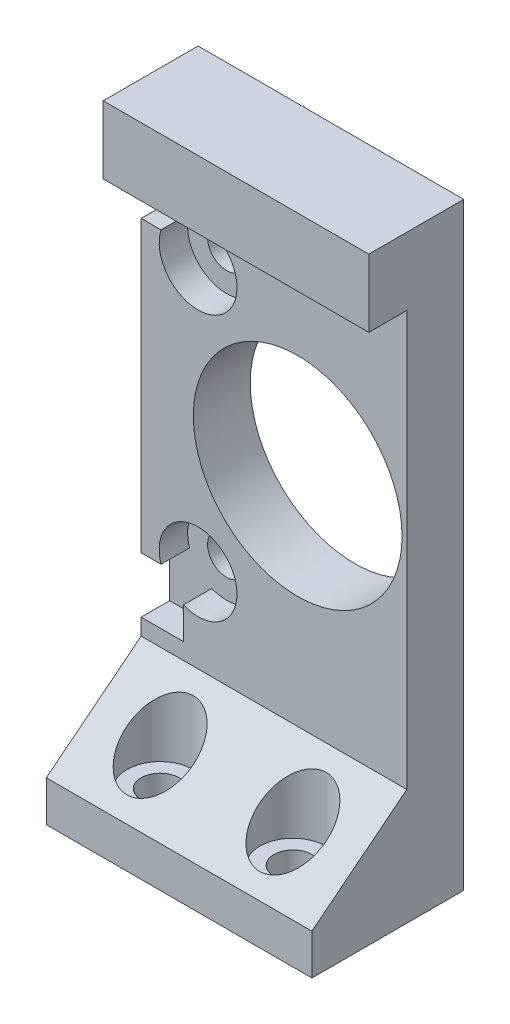
SolidWorks part; units mm, degrees
material "ABS"
ref_plane "Front Plane" through (0, 0, 0) normal (0, 0, 1) x (1, 0, 0)
ref_plane "Top Plane" through (0, 0, 0) normal (0, 1, 0) x (1, 0, 0)
ref_plane "Right Plane" through (0, 0, 0) normal (1, 0, 0) x (0, 0, -1)
sketch "Sketch1" plane through (0, 0, 0) normal (0, 0, 1) x (1, 0, 0)
  line L1 (-76.1871, 64.9281) -> (16.8129, 64.9281)
  line L2 (-76.1871, 64.9281) -> (-76.1871, -35.0719)
  line L3 (-76.1871, -35.0719) -> (16.8129, -35.0719)
  line L4 (16.8129, 64.9281) -> (16.8129, -35.0719)
  dimension "D1" = 93
  dimension "D2" = 100
extrude "Boss-Extrude2" add sketch "Sketch1" along normal blind 10 contours L1 L4 L3 L2
sketch "Sketch3" plane through (0, 0, 0) normal (0, 0, -1) x (-1, 0, 0)
  line L0 (76.1871, -35.0719) -> (-16.8129, -35.0719) construction
  line L1 (-16.8129, 64.9281) -> (-6.8129, 64.9281)
  line L2 (-16.8129, 64.9281) -> (-16.8129, -35.0719)
  line L3 (-16.8129, -35.0719) -> (-6.8129, -35.0719)
  line L4 (-6.8129, 64.9281) -> (-6.8129, -35.0719)
  line L5 (-16.8129, 64.9281) -> (-16.8129, -35.0719) construction
  dimension "D1" = 0
  dimension "D2" = 0
  dimension "D3" = 10
  dimension "D4" = 100
sketch "Sketch4" plane through (16.8129, 0, 0) normal (1, 0, 0) x (0, 0, -1)
  line L0 (-10, 64.9281) -> (-10, -35.0719) construction
  line L1 (-10, -5.0719) -> (0.01, -5.0719)
  line L2 (-10, -5.0719) -> (-10, -20.0719)
  line L3 (-10, -20.0719) -> (0.01, -20.0719)
  line L4 (0.01, -5.0719) -> (0.01, -20.0719)
  line L6 (-10, -35.0719) -> (0, -35.0719) construction
  dimension "D1" = 15
  dimension "D2" = 15
extrude "Boss-Extrude4" add sketch "Sketch4" along normal blind 24
sketch "Sketch5" plane through (0, -5.0719, 0) normal (0, 1, 0) x (1, 0, 0)
  line L0 (40.8129, -10) -> (16.8129, -10) construction
  line L2 (16.8129, 0) -> (16.8129, -10) construction
  circle A0 centre (26.8129, -5) radius 2
  dimension "D2" = 4
  dimension "D3" = 10
  dimension "D1" = 5
extrude "Cut-Extrude1" cut sketch "Sketch5" against normal blind 50
sketch "Sketch6" plane through (0, 0, 10) normal (0, 0, -1) x (-1, 0, 0)
  line L2 (76.1871, -35.0719) -> (-16.8129, -35.0719) construction
  line L3 (-16.8129, 64.9281) -> (-16.8129, -35.0719) construction
  circle A0 centre (-1.8129, -24.5719) radius 7.5
  dimension "D1" = 15
  dimension "D2" = 10.5
  dimension "D3" = 15
sketch "Sketch7" plane through (0, 0, 0) normal (0, 0, -1) x (-1, 0, 0)
  circle A0 centre (24.1871, 36.9281) radius 11
  circle A1 centre (24.1871, 36.9281) radius 9.3 construction
  dimension "D1" = 22
extrude "Cut-Extrude3" cut sketch "Sketch7" against normal blind 50
sketch "Sketch14" plane through (0, 0, 10) normal (0, 0, 1) x (1, 0, 0)
  line L0 (16.8129, 64.9281) -> (16.8129, -5.0719) construction
  line L1 (-44.6871, 15.7891) -> (16.8129, 15.7891)
  line L2 (-44.6871, 15.7891) -> (-44.6871, 57.7891)
  line L3 (-44.6871, 57.7891) -> (16.8129, 57.7891)
  line L4 (16.8129, 15.7891) -> (16.8129, 57.7891)
  dimension "D1" = 42
  dimension "D3" = 61.5
extrude "Cut-Extrude8" cut sketch "Sketch14" against normal blind 4
sketch "Sketch15" plane through (0, 0, 0) normal (0, 0, -1) x (-1, 0, 0)
  circle A0 centre (24.1871, 36.9281) radius 10
  circle A1 centre (24.1871, 36.9281) radius 11 construction
  dimension "D1" = 20
  dimension "D2" = 0
sketch "Sketch16" plane through (0, 0, 10) normal (0, 0, 1) x (1, 0, 0)
  line L0 (-43.6871, 56.9281) -> (14.3129, 56.9281) construction
  line L1 (-44.1871, 57.3281) -> (16.8129, 57.3281)
  line L2 (-44.1871, 57.3281) -> (-44.1871, 64.9281)
  line L3 (-44.1871, 64.9281) -> (16.8129, 64.9281)
  line L4 (16.8129, 57.3281) -> (16.8129, 64.9281)
  dimension "D1" = 0.4
sketch "Sketch17" plane through (0, 0, 10) normal (0, 0, 1) x (1, 0, 0)
  line L0 (16.8129, 15.7891) -> (16.8129, -5.0719) construction
  line L1 (-44.1871, 16.7281) -> (16.8129, 16.7281)
  line L2 (-44.1871, 16.7281) -> (-44.1871, -20.0719)
  line L3 (-44.1871, -20.0719) -> (16.8129, -20.0719)
  line L4 (16.8129, 16.7281) -> (16.8129, -20.0719)
  line L5 (-43.6871, 16.9281) -> (14.3129, 16.9281) construction
  line L6 (40.8129, -20.0719) -> (16.8129, -20.0719) construction
  line L9 (16.8129, -20.0719) -> (40.8129, -20.0719)
  line L10 (16.8129, -20.0719) -> (16.8129, -5.0719)
  line L11 (16.8129, -5.0719) -> (40.8129, -5.0719)
  line L12 (40.8129, -20.0719) -> (40.8129, -5.0719)
  line L13 (16.8129, -20.0719) -> (40.8129, -5.0719) construction
  line L14 (16.8129, -5.0719) -> (40.8129, -20.0719) construction
  point P16 (28.8129, -12.5719)
  dimension "D1" = 0.2
  dimension "D2" = 0
sketch "Sketch19" plane through (0, 0, 0) normal (0, 0, -1) x (-1, 0, 0)
  line L1 (-16.8129, 64.9281) -> (-16.8129, -35.0719) construction
  circle A0 centre (53.1871, 36.9281) radius 11
  circle A1 centre (24.1871, 36.9281) radius 10 construction
  dimension "D1" = 22
  dimension "D3" = 0
  dimension "D2" = 70
extrude "Cut-Extrude11" cut sketch "Sketch19" against normal blind 15
sketch "Sketch20" plane through (0, 0, 6) normal (0, 0, 1) x (1, 0, 0)
  circle A0 centre (-34.6871, 50.9281) radius 2
  circle A1 centre (5.3129, 50.9281) radius 2
  circle A2 centre (-34.6871, 22.9281) radius 2
  circle A3 centre (5.3129, 22.9281) radius 2
  arc A5 (-27.0471, 34.1316) -> (-27.0471, 39.7246) centre (-24.1871, 36.9281) ccw construction
  circle A6 centre (-24.1871, 36.9281) radius 11 construction
  dimension "D1" = 4
  dimension "D2" = 4
  dimension "D3" = 4
  dimension "D4" = 4
  dimension "D5" = 0
  dimension "D6" = 28
  dimension "D7" = 0
  dimension "D8" = 40
  dimension "D9" = 14
  dimension "D10" = 10.5
  dimension "D11" = 28
  dimension "D12" = 40
extrude "Cut-Extrude12" cut sketch "Sketch20" against normal blind 10
sketch "Sketch8" plane through (0, 64.9281, 0) normal (0, 1, 0) x (1, 0, 0)
  line L0 (-76.1871, -10) -> (16.8129, -10) construction
  line L5 (16.8129, 0) -> (12.3014, -10) construction
  line L6 (16.8129, -10) -> (7.8859, 0) construction
  line L8 (16.8129, -10) -> (16.8129, 0) construction
  line L9 (-76.1871, 0) -> (16.8129, 0) construction
  circle A0 centre (11.8129, -7) radius 1.4
  circle A1 centre (-13.1871, -7) radius 1.4
  point P4 (13.816, -6.6429)
  dimension "D1" = 25
  dimension "D2" = 5
  dimension "D3" = 2.8
  dimension "D4" = 7
  dimension "D5" = 7
sketch "Sketch21" plane through (0, 0, 0) normal (0, 0, -1) x (-1, 0, 0)
  line L1 (76.1871, 64.9281) -> (36.1871, 64.9281)
  line L2 (76.1871, 64.9281) -> (76.1871, 58.9281)
  line L3 (76.1871, 58.9281) -> (36.1871, 58.9281)
  line L4 (36.1871, 64.9281) -> (36.1871, 58.9281)
  dimension "D1" = 6
  dimension "D2" = 40
extrude "Boss-Extrude5" add sketch "Sketch21" along normal blind 27
sketch "Sketch22" plane through (0, 58.9281, 0) normal (0, -1, 0) x (1, 0, 0)
  line L0 (-76.1871, -27) -> (-76.1871, 0) construction
  line L1 (-36.1871, -27) -> (-76.1871, -27)
  line L2 (-36.1871, -27) -> (-36.1871, -20.7)
  line L3 (-36.1871, -20.7) -> (-76.1871, -20.7)
  line L4 (-76.1871, -27) -> (-76.1871, -20.7)
  dimension "D1" = 6.3
extrude "Boss-Extrude7" add sketch "Sketch22" along normal blind 40
sketch "Sketch23" plane through (0, 0, 10) normal (0, 0, 1) x (1, 0, 0)
  circle A0 centre (-53.1871, 36.9281) radius 8
  arc A1 (-44.6871, 43.9102) -> (-44.6871, 29.9459) centre (-53.1871, 36.9281) ccw construction
  dimension "D1" = 16
  dimension "D2" = 0
extrude "Cut-Extrude13" cut sketch "Sketch23" against normal blind 40
sketch "Sketch24" plane through (0, 0, 10) normal (0, 0, 1) x (1, 0, 0)
  line L1 (-76.1871, -35.0719) -> (42.0908, -35.0719)
  line L2 (-76.1871, -35.0719) -> (-76.1871, 6.7281)
  line L3 (-76.1871, 6.7281) -> (42.0908, 6.7281)
  line L4 (42.0908, -35.0719) -> (42.0908, 6.7281)
  dimension "D1" = 41.8
extrude "Cut-Extrude14" cut sketch "Sketch24" against normal blind 40
sketch "Sketch25" plane through (0, 0, 10) normal (0, 0, 1) x (1, 0, 0)
  line L5 (-44.6871, 29.9459) -> (-44.6871, 15.7891) construction
  line L6 (-76.1871, 6.7281) -> (-44.6871, 6.7281)
  line L7 (-76.1871, 6.7281) -> (-76.1871, 29.9281)
  line L8 (-76.1871, 29.9281) -> (-44.6871, 29.9281)
  line L9 (-44.6871, 6.7281) -> (-44.6871, 29.9281)
  arc A2 (-44.6871, 43.9102) -> (-44.6871, 29.9459) centre (-53.1871, 36.9281) ccw construction
  dimension "D1" = 7
extrude "Cut-Extrude15" cut sketch "Sketch25" against normal blind 20
sketch "Sketch26" plane through (0, 0, 6) normal (0, 0, 1) x (1, 0, 0)
  line L1 (-44.6871, 15.7891) -> (-36.2375, 15.7891)
  line L2 (-44.6871, 15.7891) -> (-44.6871, 21.6647)
  line L3 (-44.6871, 21.6647) -> (-36.2375, 21.6647)
  line L4 (-36.2375, 15.7891) -> (-36.2375, 21.6647)
  line L5 (-44.6871, 57.7891) -> (-36.2375, 57.7891)
  line L6 (-44.6871, 57.7891) -> (-44.6871, 52.1914)
  line L7 (-44.6871, 52.1914) -> (-36.2375, 52.1914)
  line L8 (-36.2375, 57.7891) -> (-36.2375, 52.1914)
  line L9 (6.8634, 52.1914) -> (14.3021, 52.1914)
  line L10 (6.8634, 52.1914) -> (6.8634, 57.7891)
  line L11 (6.8634, 57.7891) -> (14.3021, 57.7891)
  line L12 (14.3021, 52.1914) -> (14.3021, 57.7891)
  line L13 (6.8634, 20.9281) -> (14.3021, 20.9281)
  line L14 (6.8634, 20.9281) -> (6.8634, 15.7891)
  line L15 (6.8634, 15.7891) -> (14.3021, 15.7891)
  line L16 (14.3021, 20.9281) -> (14.3021, 15.7891)
  circle A0 centre (-34.6871, 22.9281) radius 2 construction
  circle A1 centre (-34.6871, 50.9281) radius 2 construction
  circle A2 centre (5.3129, 50.9281) radius 2 construction
  circle A3 centre (5.3129, 22.9281) radius 4
  circle A4 centre (5.3129, 50.9281) radius 4
  circle A5 centre (-34.6871, 50.9281) radius 4
  circle A6 centre (-34.6871, 22.9281) radius 4
  circle A7 centre (5.3129, 50.9281) radius 4
  circle A8 centre (5.3129, 22.9281) radius 4
  circle A9 centre (-34.6871, 50.9281) radius 4
  circle A10 centre (-34.6871, 22.9281) radius 4
  line M5 (-44.6871, 57.7891) -> (-44.6871, 43.9102)
  line M8 (-44.6871, 29.9281) -> (-44.6871, 15.7891)
  line M9 (-44.6871, 15.7891) -> (16.8129, 15.7891)
  line M11 (16.8129, 57.7891) -> (-44.6871, 57.7891)
  dimension "D1" = 8
  dimension "D2" = 8
  dimension "D3" = 8
  dimension "D4" = 8
extrude "Cut-Extrude18" cut sketch "Sketch26" against normal blind 3 contours A4 L9 L12 L10 M11 | A3 L14 L16 L13 M9 | A5 L8 L7 M11 M5 | A6 L3 L4 M8 M9
sketch "Sketch27" plane through (0, 0, 6) normal (0, 0, 1) x (1, 0, 0)
  circle A0 centre (5.3129, 50.9281) radius 4.1
  circle A1 centre (5.3129, 22.9281) radius 4
  circle A2 centre (-34.6871, 50.9281) radius 4.1
  circle A3 centre (-34.6871, 22.9281) radius 4.1
  dimension "D1" = 8.2
  dimension "D2" = 8.2
  dimension "D3" = 8
  dimension "D4" = 8.2
extrude "Cut-Extrude29" cut sketch "Sketch27" against normal blind 3
sketch "Sketch28" plane through (0, 0, 0) normal (0, 0, -1) x (-1, 0, 0)
  line L5 (-16.8129, 6.7281) -> (44.6871, 6.7281) construction
  line L6 (-16.8129, 64.9281) -> (12.6871, 64.9281)
  line L7 (-16.8129, 64.9281) -> (-16.8129, 6.7281)
  line L8 (-16.8129, 6.7281) -> (12.6871, 6.7281)
  line L9 (12.6871, 64.9281) -> (12.6871, 6.7281)
  circle A1 centre (34.6871, 22.9281) radius 2 construction
  dimension "D1" = 22
extrude "Cut-Extrude30" cut sketch "Sketch28" against normal blind 23
sketch "Sketch29" plane through (0, 15.7891, 0) normal (0, 1, 0) x (1, 0, 0)
  line L1 (-44.6871, -10) -> (-12.6871, -10)
  line L2 (-44.6871, -10) -> (-44.6871, -6)
  line L3 (-44.6871, -6) -> (-12.6871, -6)
  line L4 (-12.6871, -10) -> (-12.6871, -6)
extrude "Cut-Extrude31" cut sketch "Sketch29" against normal blind 23
sketch "Sketch31" plane through (0, 6.7281, 0) normal (0, -1, 0) x (1, 0, 0)
  line L1 (-44.6871, 6) -> (-12.6871, 6)
  line L2 (-44.6871, 6) -> (-44.6871, 0)
  line L3 (-44.6871, 0) -> (-12.6871, 0)
  line L4 (-12.6871, 6) -> (-12.6871, 0)
extrude "Boss-Extrude9" add sketch "Sketch31" along normal blind 6.6
sketch "Sketch32" plane through (0, 0, 6) normal (0, 0, 1) x (1, 0, 0)
  line L0 (-12.6871, 0.1281) -> (-12.6871, 57.7891) construction
  line L1 (-44.6871, 0.1281) -> (-12.6871, 0.1281)
  line L2 (-44.6871, 0.1281) -> (-44.6871, 6.1281)
  line L3 (-44.6871, 6.1281) -> (-12.6871, 6.1281)
  line L4 (-12.6871, 0.1281) -> (-12.6871, 6.1281)
  dimension "D1" = 6
extrude "Boss-Extrude10" add sketch "Sketch32" along normal blind 10
sketch "Sketch33" plane through (0, 6.1281, 0) normal (0, 1, 0) x (1, 0, 0)
  line L0 (-12.6871, -16) -> (-44.6871, -16) construction
  line L1 (-44.6871, -16) -> (-44.6871, -6) construction
  line L2 (-12.6871, -16) -> (-12.6871, -6) construction
  circle A0 centre (-33.6871, -11) radius 2
  circle A1 centre (-19.6871, -11) radius 2
  point P8 (-44.6871, -11)
  dimension "D1" = 4
  dimension "D2" = 4
  dimension "D3" = 0
  dimension "D4" = 5
  dimension "D5" = 11
  dimension "D6" = 7
extrude "Cut-Extrude32" cut sketch "Sketch33" against normal blind 10
sketch "Sketch34" plane through (-12.6871, 0, 0) normal (1, 0, 0) x (0, 0, -1)
  line L0 (-16, 6.1281) -> (-6, 6.1281)
  line L1 (-6, 6.1281) -> (-6, 14.0584)
  line L2 (-6, 6.1281) -> (-6, 57.7891) construction
  line L3 (-6, 14.0584) -> (-16, 6.1281)
extrude "Boss-Extrude11" add sketch "Sketch34" against normal up to vertex
sketch "Sketch35" plane through (0, 6.1281, 0) normal (0, -1, 0) x (1, 0, 0)
  circle A0 centre (-19.6871, 11) radius 3.5
  circle A1 centre (-33.6871, 11) radius 3.5
  dimension "D1" = 7
  dimension "D2" = 7
extrude "Cut-Extrude33" cut sketch "Sketch35" against normal blind 10
sketch "Sketch36" plane through (-36.1871, 0, 0) normal (1, 0, 0) x (0, 0, -1)
  line L1 (0, 64.9281) -> (27, 64.9281)
  line L2 (0, 64.9281) -> (0, 18.9281)
  line L3 (0, 18.9281) -> (27, 18.9281)
  line L4 (27, 64.9281) -> (27, 18.9281)
extrude "Cut-Extrude34" cut sketch "Sketch36" against normal blind 50
sketch "Sketch38" plane through (0, 0, 10) normal (0, 0, 1) x (1, 0, 0)
  line L0 (-76.1871, 64.9281) -> (-12.6871, 64.9281) construction
  line L1 (-76.1871, 29.9281) -> (-44.4371, 29.9281)
  line L2 (-76.1871, 29.9281) -> (-76.1871, 64.9281)
  line L3 (-76.1871, 64.9281) -> (-44.4371, 64.9281)
  line L4 (-44.4371, 29.9281) -> (-44.4371, 64.9281)
extrude "Cut-Extrude35" cut sketch "Sketch38" against normal blind 50
sketch "Sketch40" plane through (0, 0, 16) normal (0, 0, 1) x (1, 0, 0)
  line L1 (-44.6871, 0.1281) -> (-40.6871, 0.1281)
  line L2 (-44.6871, 0.1281) -> (-44.6871, 77.9464)
  line L3 (-44.6871, 77.9464) -> (-40.6871, 77.9464)
  line L4 (-40.6871, 0.1281) -> (-40.6871, 77.9464)
  dimension "D1" = 4
extrude "Cut-Extrude37" cut sketch "Sketch40" against normal blind 110
sketch "Sketch41" plane through (0, 0, 16) normal (0, 0, 1) x (1, 0, 0)
  line L1 (-40.6871, 0.1281) -> (-12.6871, 0.1281)
  line L2 (-40.6871, 0.1281) -> (-40.6871, 1.8481)
  line L3 (-40.6871, 1.8481) -> (-12.6871, 1.8481)
  line L4 (-12.6871, 0.1281) -> (-12.6871, 1.8481)
  dimension "D1" = 1.72
extrude "Cut-Extrude38" cut sketch "Sketch41" against normal blind 50
